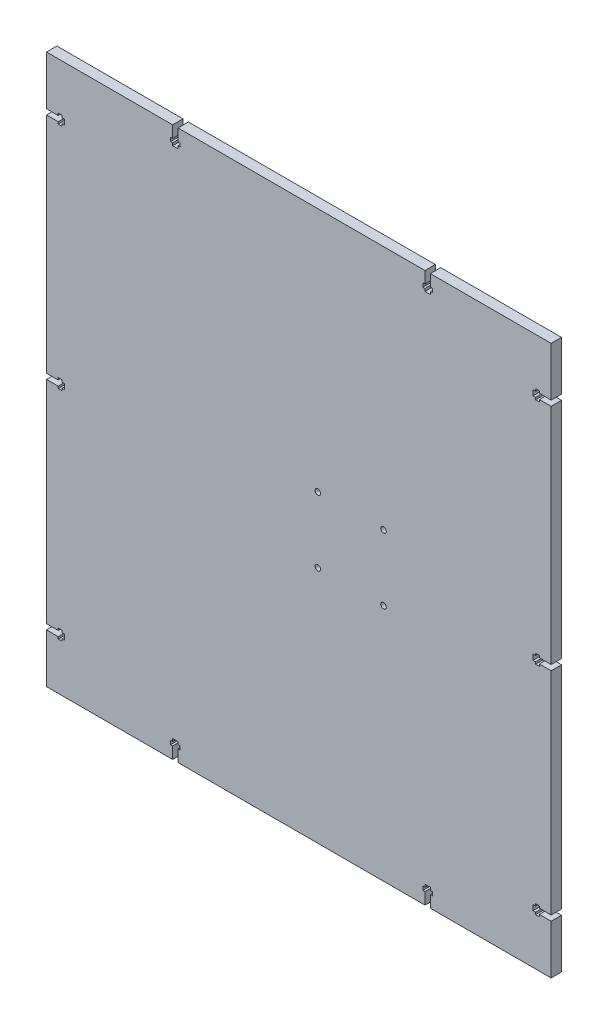
SolidWorks part; units mm, degrees
material "Клен"
ref_plane "Спереди" through (0, 0, 0) normal (0, 0, 1) x (1, 0, 0)
ref_plane "Сверху" through (0, 0, 0) normal (0, 1, 0) x (1, 0, 0)
ref_plane "Справа" through (0, 0, 0) normal (1, 0, 0) x (0, 0, -1)
sketch "Эскиз1" plane through (0, 0, 0) normal (0, 0, 1) x (1, 0, 0)
  line L1 (0, 0) -> (73, 0)
  line L2 (0, 0) -> (0, -28.45)
  line L3 (0, -318) -> (73, -318)
  line L4 (292, 0) -> (292, -28.45)
  line L15 (146, 38.6612) -> (146, -369.0135) construction
  line L16 (338.8892, -160.95) -> (-53.634, -160.95) construction
  line L17 (-48.9358, -30) -> (338.8892, -30) construction
  line L18 (-48.9358, -289.55) -> (329.134, -289.55) construction
  line L76 (0, -289.55) -> (0, -318)
  line L80 (73, 38.6612) -> (73, -369.0135) construction
  line L81 (219, 38.6612) -> (219, -369.0135) construction
  line L82 (76.1, 0) -> (219, 0)
  line L83 (222.1, 0) -> (292, 0)
  line L84 (76.1, -318) -> (219, -318)
  line L85 (222.1, -318) -> (292, -318)
  line L86 (338.8892, -28.45) -> (-48.9358, -28.45) construction
  line L87 (285.2, -28.45) -> (285.2, -27.25)
  line L88 (283, -32.75) -> (285.2, -32.75)
  line L89 (283, -28.45) -> (281.5, -28.45)
  line L90 (285.2, -27.25) -> (283, -27.25)
  line L91 (292, -28.45) -> (285.2, -28.45)
  line L92 (281.5, -31.55) -> (283, -31.55)
  line L93 (222.1, -6.8) -> (222.1, 0)
  line L94 (222.1, -9) -> (223.3, -9)
  line L95 (219, -10.5) -> (222.1, -10.5)
  line L96 (222.1, -10.5) -> (222.1, -9)
  line L97 (219, 0) -> (219, -6.8)
  line L98 (219, -6.8) -> (217.8, -6.8)
  line L99 (223.3, -9) -> (223.3, -6.8)
  line L100 (217.8, -6.8) -> (217.8, -9)
  line L101 (223.3, -6.8) -> (222.1, -6.8)
  line L102 (217.8, -9) -> (219, -9)
  line L103 (219, -9) -> (219, -10.5)
  line L104 (76.1, -6.8) -> (76.1, 0)
  line L105 (76.1, -9) -> (77.3, -9)
  line L106 (73, -10.5) -> (76.1, -10.5)
  line L107 (76.1, -10.5) -> (76.1, -9)
  line L108 (73, 0) -> (73, -6.8)
  line L109 (73, -6.8) -> (71.8, -6.8)
  line L110 (77.3, -9) -> (77.3, -6.8)
  line L111 (71.8, -6.8) -> (71.8, -9)
  line L112 (77.3, -6.8) -> (76.1, -6.8)
  line L113 (71.8, -9) -> (73, -9)
  line L114 (73, -9) -> (73, -10.5)
  line L115 (73, -309) -> (73, -307.5)
  line L116 (71.8, -309) -> (73, -309)
  line L117 (77.3, -311.2) -> (76.1, -311.2)
  line L118 (71.8, -311.2) -> (71.8, -309)
  line L119 (77.3, -309) -> (77.3, -311.2)
  line L120 (73, -311.2) -> (71.8, -311.2)
  line L121 (73, -318) -> (73, -311.2)
  line L122 (76.1, -307.5) -> (76.1, -309)
  line L123 (73, -307.5) -> (76.1, -307.5)
  line L124 (76.1, -309) -> (77.3, -309)
  line L125 (76.1, -311.2) -> (76.1, -318)
  line L126 (219, -309) -> (219, -307.5)
  line L127 (217.8, -309) -> (219, -309)
  line L128 (223.3, -311.2) -> (222.1, -311.2)
  line L129 (217.8, -311.2) -> (217.8, -309)
  line L130 (223.3, -309) -> (223.3, -311.2)
  line L131 (219, -311.2) -> (217.8, -311.2)
  line L132 (219, -318) -> (219, -311.2)
  line L133 (222.1, -307.5) -> (222.1, -309)
  line L134 (219, -307.5) -> (222.1, -307.5)
  line L135 (222.1, -309) -> (223.3, -309)
  line L136 (222.1, -311.2) -> (222.1, -318)
  line L137 (285.2, -32.75) -> (285.2, -31.55)
  line L138 (285.2, -31.55) -> (292, -31.55)
  line L139 (281.5, -28.45) -> (281.5, -31.55)
  line L140 (283, -27.25) -> (283, -28.45)
  line L141 (283, -31.55) -> (283, -32.75)
  line L142 (292, -33.1) -> (292, -31.55)
  line L143 (285.2, -286.45) -> (285.2, -285.25)
  line L144 (285.2, -289.55) -> (292, -289.55)
  line L145 (281.5, -286.45) -> (281.5, -289.55)
  line L146 (283, -285.25) -> (283, -286.45)
  line L147 (283, -286.45) -> (281.5, -286.45)
  line L148 (281.5, -289.55) -> (283, -289.55)
  line L149 (292, -286.45) -> (285.2, -286.45)
  line L150 (285.2, -285.25) -> (283, -285.25)
  line L151 (283, -289.55) -> (283, -290.75)
  line L152 (283, -290.75) -> (285.2, -290.75)
  line L153 (285.2, -290.75) -> (285.2, -289.55)
  line L155 (292, -289.55) -> (292, -318)
  line L157 (9, -31.55) -> (9, -32.75)
  line L158 (9, -27.25) -> (9, -28.45)
  line L159 (10.5, -28.45) -> (10.5, -31.55)
  line L160 (6.8, -31.55) -> (0, -31.55)
  line L161 (6.8, -32.75) -> (6.8, -31.55)
  line L162 (10.5, -31.55) -> (9, -31.55)
  line L163 (0, -28.45) -> (6.8, -28.45)
  line L164 (6.8, -27.25) -> (9, -27.25)
  line L165 (9, -28.45) -> (10.5, -28.45)
  line L166 (9, -32.75) -> (6.8, -32.75)
  line L167 (6.8, -28.45) -> (6.8, -27.25)
  line L179 (6.8, -290.75) -> (6.8, -289.55)
  line L180 (9, -290.75) -> (6.8, -290.75)
  line L181 (9, -289.55) -> (9, -290.75)
  line L182 (6.8, -285.25) -> (9, -285.25)
  line L183 (0, -286.45) -> (6.8, -286.45)
  line L184 (10.5, -289.55) -> (9, -289.55)
  line L185 (9, -286.45) -> (10.5, -286.45)
  line L186 (9, -285.25) -> (9, -286.45)
  line L187 (10.5, -286.45) -> (10.5, -289.55)
  line L188 (6.8, -289.55) -> (0, -289.55)
  line L189 (6.8, -286.45) -> (6.8, -285.25)
  line L191 (292, -33.1) -> (292, -160.95)
  line L192 (281.5, -160.95) -> (281.5, -164.05)
  line L193 (281.5, -164.05) -> (283, -164.05)
  line L194 (283, -160.95) -> (281.5, -160.95)
  line L195 (285.2, -164.05) -> (292, -164.05)
  line L196 (283, -165.25) -> (285.2, -165.25)
  line L197 (285.2, -165.25) -> (285.2, -164.05)
  line L198 (285.2, -159.75) -> (283, -159.75)
  line L199 (283, -159.75) -> (283, -160.95)
  line L200 (292, -160.95) -> (285.2, -160.95)
  line L201 (285.2, -160.95) -> (285.2, -159.75)
  line L202 (283, -164.05) -> (283, -165.25)
  line L203 (292, -164.05) -> (292, -286.45)
  line L204 (9, -164.05) -> (9, -165.25)
  line L205 (6.8, -160.95) -> (6.8, -159.75)
  line L206 (0, -160.95) -> (6.8, -160.95)
  line L207 (9, -159.75) -> (9, -160.95)
  line L208 (6.8, -159.75) -> (9, -159.75)
  line L209 (6.8, -165.25) -> (6.8, -164.05)
  line L210 (9, -165.25) -> (6.8, -165.25)
  line L211 (6.8, -164.05) -> (0, -164.05)
  line L212 (9, -160.95) -> (10.5, -160.95)
  line L213 (10.5, -164.05) -> (9, -164.05)
  line L214 (10.5, -160.95) -> (10.5, -164.05)
  line L215 (0, -31.55) -> (0, -160.95)
  line L216 (0, -286.45) -> (0, -164.05)
  line L217 (119.0367, -141.95) -> (174.301, -141.95) construction
  line L219 (97, -80.4342) -> (97, -210.3267) construction
  line L220 (195, -80.4342) -> (195, -214.5168) construction
  circle A4 centre (157, -141.95) radius 1.6
  circle A5 centre (195, -141.95) radius 1.6
  circle A6 centre (195, -179.95) radius 1.6
  circle A7 centre (157, -179.95) radius 1.6
  dimension "D1" = 292
  dimension "D2" = 318
  dimension "D3" = 30
  dimension "D4" = 73
  dimension "D5" = 73
  dimension "D6" = 28.45
  dimension "D7" = 28.45
  dimension "D8" = 160.95
  dimension "D10" = 19
  dimension "D12" = 97
  dimension "D13" = 97
extrude "Бобышка-Вытянуть1" add sketch "Эскиз1" along normal blind 6
